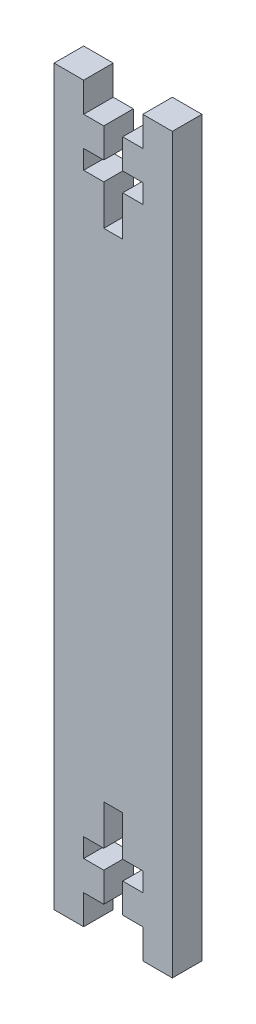
SolidWorks part; units mm, degrees
ref_plane "Front Plane" through (0, 0, 0) normal (0, 0, 1) x (1, 0, 0)
ref_plane "Top Plane" through (0, 0, 0) normal (0, 1, 0) x (1, 0, 0)
ref_plane "Right Plane" through (0, 0, 0) normal (1, 0, 0) x (0, 0, -1)
sketch "Sketch1" plane through (0, 0, 0) normal (0, 0, 1) x (1, 0, 0)
  line L0 (6.35, 78.74) -> (12.7, 78.74)
  line L1 (-12.7, -78.74) -> (-6.35, -78.74)
  line L2 (-12.7, -78.74) -> (-12.7, 78.74)
  line L3 (-12.7, 78.74) -> (-6.35, 78.74)
  line L4 (12.7, -78.74) -> (12.7, 78.74)
  line L5 (-12.7, -78.74) -> (12.7, 78.74) construction
  line L6 (-12.7, 78.74) -> (12.7, -78.74) construction
  line L8 (-6.35, 78.74) -> (-6.35, 72.39)
  line L9 (-6.35, 72.39) -> (-2.032, 72.39)
  line L10 (6.35, 78.74) -> (6.35, 72.39)
  line L11 (6.35, -78.74) -> (12.7, -78.74)
  line L13 (-6.35, -78.74) -> (-6.35, -72.39)
  line L14 (-6.35, -72.39) -> (-2.032, -72.39)
  line L15 (6.35, -78.74) -> (6.35, -72.39)
  line L16 (2.032, -72.39) -> (6.35, -72.39)
  line L18 (-2.032, -72.39) -> (-2.032, -66.04)
  line L19 (-2.032, -53.34) -> (2.032, -53.34)
  line L20 (2.032, -72.39) -> (2.032, -66.04)
  line L21 (2.032, 72.39) -> (6.35, 72.39)
  line L23 (-2.032, 72.39) -> (-2.032, 66.04)
  line L24 (-2.032, 53.34) -> (2.032, 53.34)
  line L25 (2.032, 72.39) -> (2.032, 66.04)
  line L26 (2.032, 61.976) -> (2.032, 53.34)
  line L27 (-2.032, 66.04) -> (-6.35, 66.04)
  line L29 (-2.032, 61.976) -> (-6.35, 61.976)
  line L30 (-6.35, 66.04) -> (-6.35, 61.976)
  line L31 (2.032, 66.04) -> (6.35, 66.04)
  line L33 (2.032, 61.976) -> (6.35, 61.976)
  line L34 (6.35, 66.04) -> (6.35, 61.976)
  line L35 (-2.032, 61.976) -> (-2.032, 53.34)
  line L36 (2.032, -61.976) -> (6.35, -61.976)
  line L37 (-6.35, -66.04) -> (-2.032, -66.04)
  line L38 (-6.35, -66.04) -> (-6.35, -61.976)
  line L39 (-6.35, -61.976) -> (-2.032, -61.976)
  line L40 (6.35, -66.04) -> (6.35, -61.976)
  line L41 (2.032, -66.04) -> (6.35, -66.04)
  line L42 (-2.032, -61.976) -> (-2.032, -53.34)
  line L43 (2.032, -61.976) -> (2.032, -53.34)
  point P0 (0, 0)
  dimension "D1" = 157.48
  dimension "D2" = 25.4
  dimension "D3" = 12.7
  dimension "D4" = 6.35
  dimension "D5" = 6.35
  dimension "D6" = 12.7
  dimension "D7" = 4.064
  dimension "D8" = 25.4
  dimension "D9" = 25.4
  dimension "D10" = 4.064
  dimension "D11" = 4.064
  dimension "D12" = 6.35
extrude "Boss-Extrude1" add sketch "Sketch1" along normal blind 6.35
